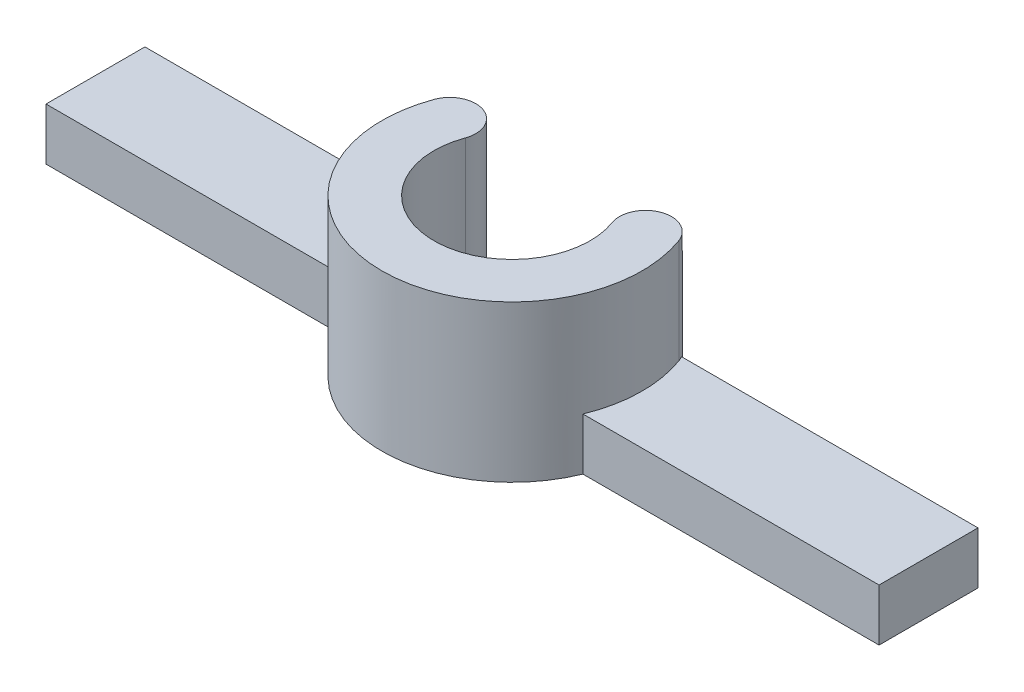
SolidWorks part; units mm, degrees
ref_plane "Front Plane" through (0, 0, 0) normal (0, 0, 1) x (1, 0, 0)
ref_plane "Top Plane" through (0, 0, 0) normal (0, 1, 0) x (1, 0, 0)
ref_plane "Right Plane" through (0, 0, 0) normal (1, 0, 0) x (0, 0, -1)
sketch "Sketch1" plane through (0, 0, 0) normal (0, 1, 0) x (1, 0, 0)
  line L0 (0, 0) -> (5, 0)
  line L1 (0, 0) -> (4.6985, 1.7101)
  line L2 (4.6985, 1.7101) -> (3.7588, 1.3681)
  line L3 (0, -55) -> (0, 55) construction
  circle A0 centre (0, 0) radius 3
  circle A1 centre (0, 0) radius 5
  arc A2 (4.6985, 1.7101) -> (2.8191, 1.0261) centre (3.7588, 1.3681) ccw
  arc A3 (-4.6985, 1.7101) -> (-2.8191, 1.0261) centre (-3.7588, 1.3681) cw
  dimension "D1" = 6
  dimension "D2" = 10
  dimension "D3" = 20
  dimension "D4" = 1
extrude "Boss-Extrude1" add sketch "Sketch1" along normal blind 6 contours A3 A1 L0 A0 | L0 A1 L1 A0 | L1 A2
sketch "Sketch2" plane through (0, 0, 0) normal (0, 1, 0) x (1, 0, 0)
  line L0 (0, 0) -> (16, 0)
  line L1 (-3.3, 0) -> (3.3, 0) construction
  line L2 (16, 0) -> (16, 1.9)
  line L3 (0, -3.3) -> (0, 3.3) construction
  line L4 (16, 1.9) -> (4.5, 1.9)
  line L5 (16, 1.9) -> (16, -1.9)
  line L6 (16, -1.9) -> (4.5, -1.9)
  line L7 (4.5, 1.9) -> (4.5, -1.9)
  line L8 (-16, -1.9) -> (-4.5, -1.9)
  line L9 (-4.5, 1.9) -> (-4.5, -1.9)
  line L10 (-16, 1.9) -> (-4.5, 1.9)
  line L11 (-16, 1.9) -> (-16, -1.9)
  dimension "D1" = 16
  dimension "D2" = 1.9
  dimension "D3" = 3.8
  dimension "D4" = 11.5
extrude "Boss-Extrude2" add sketch "Sketch2" along normal blind 2 contours L10 L11 L8 L9 | L0 L7 L6 L5 | L4 L7 L0 L2
